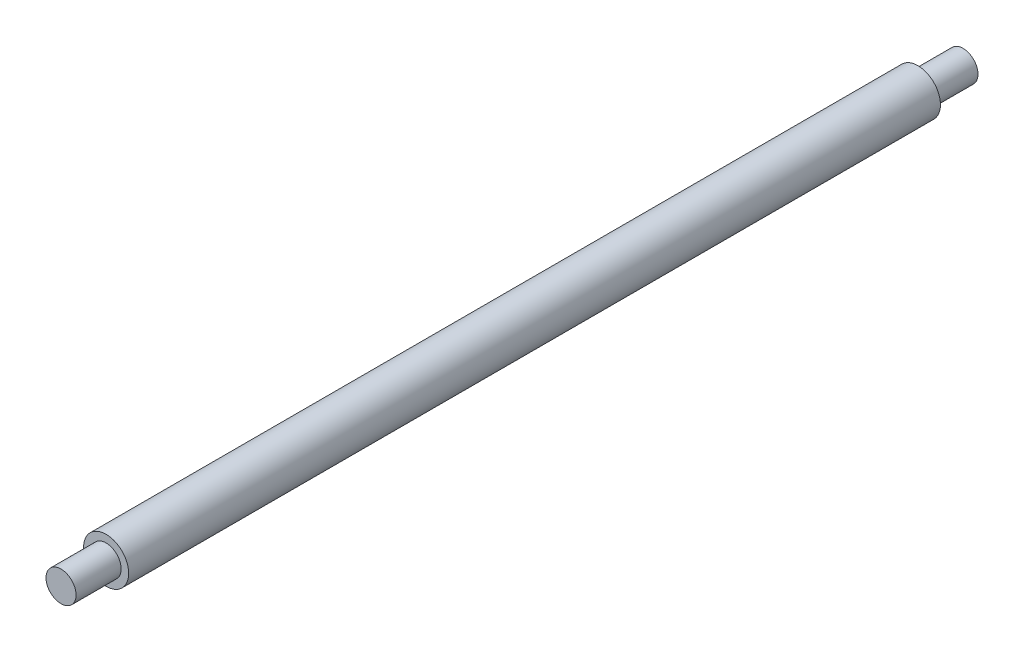
SolidWorks part; units mm, degrees
ref_plane "Front" through (0, 0, 0) normal (0, 0, 1) x (1, 0, 0)
ref_plane "Top" through (0, 0, 0) normal (0, 1, 0) x (1, 0, 0)
ref_plane "Right" through (0, 0, 0) normal (1, 0, 0) x (0, 0, -1)
sketch "Sketch1" plane through (0, 0, 0) normal (0, 0, 1) x (1, 0, 0)
  circle A0 centre (0, 0) radius 9.525
  dimension "D1" = 19.05
extrude "Boss-Extrude1" add sketch "Sketch1" along normal blind 342.9
sketch "Sketch3" plane through (0, 0, 342.9) normal (0, 0, 1) x (1, 0, 0)
  circle A0 centre (0, 0) radius 6.35
  dimension "D1" = 12.7
extrude "Boss-Extrude2" add sketch "Sketch3" along normal blind 19.05
sketch "Sketch4" plane through (0, 0, 0) normal (0, 0, -1) x (-1, 0, 0)
  circle A0 centre (0, 0) radius 6.35
  dimension "D1" = 12.7
extrude "Boss-Extrude3" add sketch "Sketch4" along normal blind 19.05
